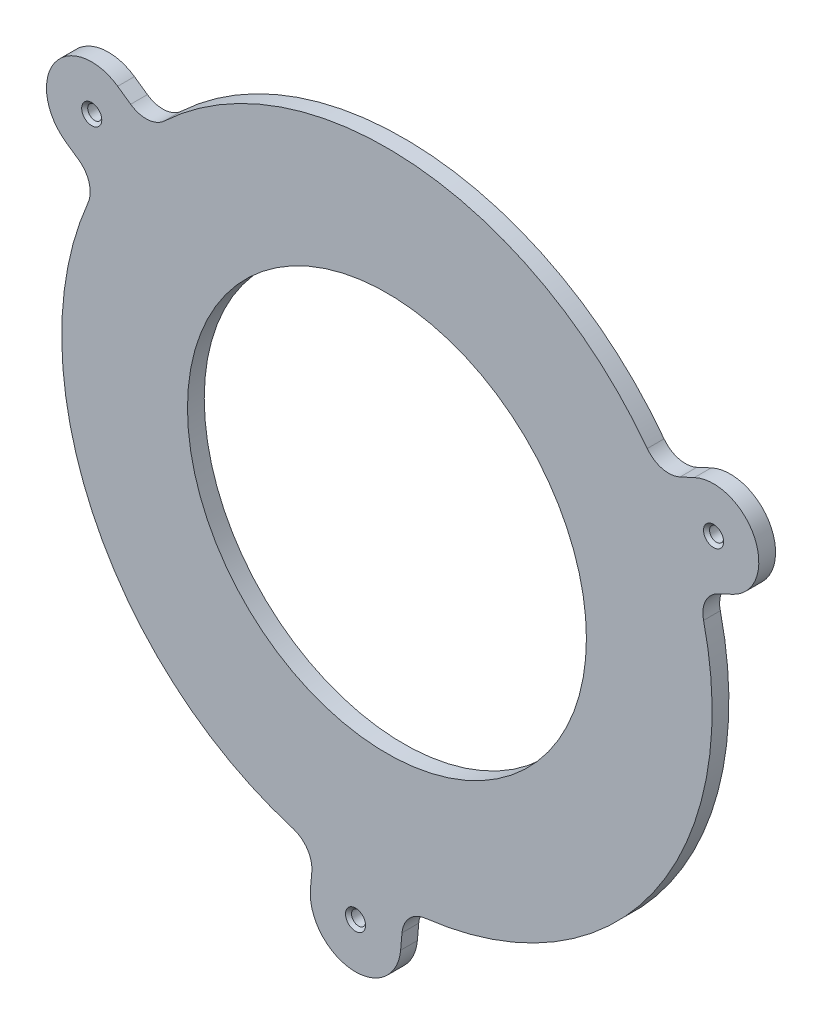
SolidWorks part; units mm, degrees
material "Plain Carbon Steel"
ref_plane "Front Plane" through (0, 0, 0) normal (0, 0, 1) x (1, 0, 0)
ref_plane "Top Plane" through (0, 0, 0) normal (0, 1, 0) x (1, 0, 0)
ref_plane "Right Plane" through (0, 0, 0) normal (1, 0, 0) x (0, 0, -1)
sketch "Layout" plane through (0, 0, 0) normal (0, 0, 1) x (1, 0, 0)
  circle A0 centre (0, 0) radius 97 construction
  circle A1 centre (0, 0) radius 62.5 construction
  circle A2 centre (0, 0) radius 57.5 construction
  dimension "D2" = 125
  dimension "D1" = 194
  dimension "D3" = 115
  dimension "D4" = 194
  dimension "D5" = 125
  dimension "D6" = 125
  dimension "D7" = 34.5
sketch "Sketch1" plane through (0, 0, 0) normal (0, 0, 1) x (1, 0, 0)
  circle A0 centre (0, 0) radius 97 construction
  circle A1 centre (0, 0) radius 62.5 construction
  circle A2 centre (0, 0) radius 62.5 construction
  circle A3 centre (0, 0) radius 97
  circle A4 centre (0, 0) radius 59.5
  dimension "D1" = 97
  dimension "D2" = 62.5
  dimension "D3" = 119
  dimension "D4" = 119
  dimension "D5" = 194
  dimension "D6" = 194
  dimension "D7" = 194
  dimension "D8" = 119
  dimension "D9" = 125
extrude "Base" add sketch "Sketch1" along normal blind 5
sketch "Sketch2" plane through (0, 0, 5) normal (0, 0, 1) x (1, 0, 0)
  line L0 (0, 0) -> (-107.5, 0) construction
  line L2 (0, 0) -> (-88.0588, 61.6595) construction
  line L3 (7.7433, 11.0586) -> (-80.3156, 72.718) construction
  line L4 (-7.7433, -11.0586) -> (-95.8021, 50.6009) construction
  line L5 (-7.7433, -11.0586) -> (7.7433, 11.0586) construction
  line L6 (-95.8021, 50.6009) -> (-80.3156, 72.718) construction
  line L7 (-95.8021, 50.6009) -> (-86.4277, 44.0369)
  line L8 (-80.3156, 72.718) -> (-70.9412, 66.154)
  circle A1 centre (0, 0) radius 107.5 construction
  circle A2 centre (0, 0) radius 97 construction
  circle A4 centre (-88.0588, 61.6595) radius 13.5 construction
  arc A5 (-70.9412, 66.154) -> (-86.4277, 44.0369) centre (0, 0) ccw
  arc A6 (-80.3156, 72.718) -> (-95.8021, 50.6009) centre (-88.0588, 61.6595) ccw
  circle A7 centre (0, 0) radius 59.5 construction
  circle A8 centre (0, 0) radius 59.5 construction
  circle A9 centre (0, 0) radius 97 construction
  point P13 (0, 0)
  point P23 (-7.7433, -11.0586)
  point P24 (-95.8021, 50.6009)
  point P26 (0, 0)
  point P31 (0, 0)
  dimension "D1" = 35
  dimension "D2" = 215
  dimension "D5" = 27
  dimension "D3" = 27
  dimension "D11" = 119
  dimension "D12" = 194
  dimension "D4" = 13.5
  dimension "D6" = 13.5
  dimension "D7" = 35
  dimension "D9" = 88.0588
  dimension "D8" = 35
  dimension "D10" = 61.6595
extrude "Tang" add sketch "Sketch2" against normal up to surface (5 mm away) up to face at (97, 0, 0)
fillet "Fillet1" radius 8 2 edges at (-86.4277, 44.0369, 2.5) (-70.9412, 66.154, 2.5)
hole_wizard "M5x0.8 Tapped Hole1" positions "3DSketch1" profile "Sketch3" tap size "M5x0.8" standard "ANSI Metric" end condition through all
sketch3d "3DSketch1"
  point P0 (-88.0588, 61.6595, 5)
sketch "Sketch3" plane through (-88.0588, 61.6595, 5) normal (1, 0, 0) x (0, -1, 0)
  line L0 (0, 0) -> (0, 5)
  line L1 (0, 5) -> (3, 5)
  line L2 (2.1, 4.1) -> (2.1, 0.9)
  line L3 (2.1, 0.9) -> (3, 0)
  line L5 (3, 0) -> (0, 0)
  line L6 (-2.1, 0.9) -> (-3, 0) construction
  line L7 (3, 5) -> (2.1, 4.1)
  line L8 (-3, 5) -> (-2.1, 4.1) construction
  line L11 (0, -6.35) -> (0, 107.95) construction
  dimension "Thru Tap Drill Dia." = 4.2
  dimension "Thru Tap Drill Depth" = 5
  dimension "Near C'Sink Dia." = 6
  dimension "Near C'Sink Angle" = 90
  dimension "Far C'Sink Dia." = 6
  dimension "Far C'Sink Angle" = 90
cosmetic thread "Hole Thread1" parameters "D2"=5
pattern_circular "CirPattern1" count 3 over 360 about axis through (0, 0, 0) along (0, 0, 1) of "Tang", "Fillet1", "M5x0.8 Tapped Hole1"
equation "\"Clutch Plate OD\"= 194"
equation "\"Clutch Plate ID\"= 125"
equation "\"Spring Housing OD\"= 115"
equation "\"Clutch Plate PCD\"= 215"
equation "\"e\"= 1"
equation "\"x\"= 1"
equation "\"y\"= 1"
equation "\"z\"= 1"
equation "\"D2@Layout\" = \"Clutch Plate ID\""
equation "\"D1@Layout\" = \"Clutch Plate OD\""
equation "\"D3@Layout\" = \"Spring Housing OD\""
